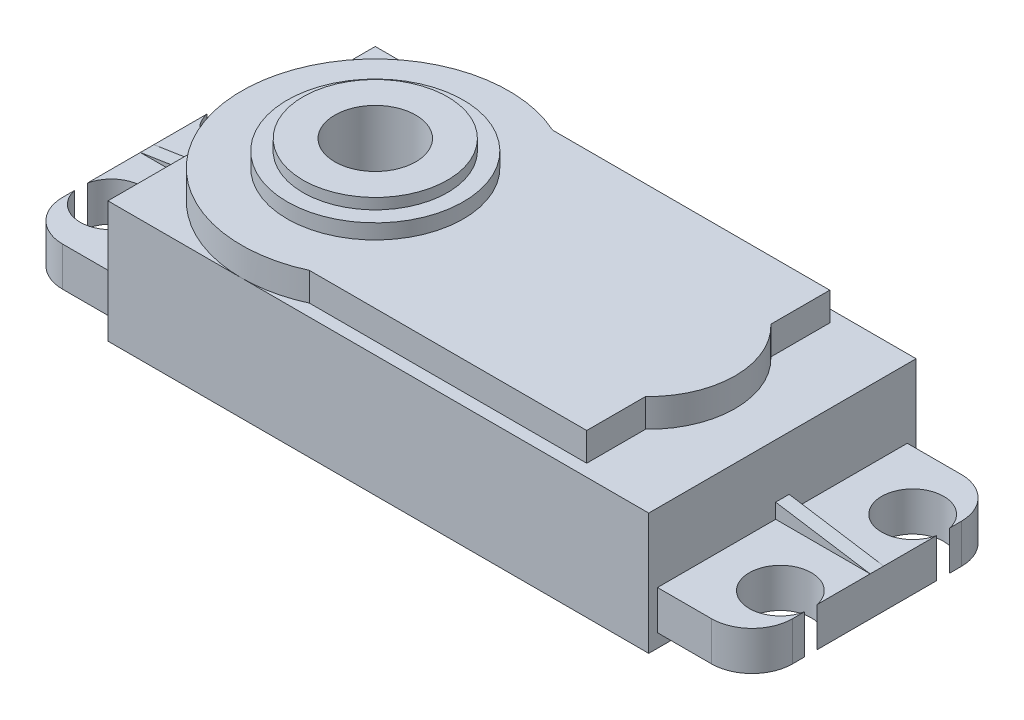
SolidWorks part; units mm, degrees
material "Калифорния"
ref_plane "Спереди" through (0, 0, 0) normal (0, 0, 1) x (1, 0, 0)
ref_plane "Сверху" through (0, 0, 0) normal (0, 1, 0) x (1, 0, 0)
ref_plane "Справа" through (0, 0, 0) normal (1, 0, 0) x (0, 0, -1)
sketch "Эскиз1" plane through (0, 0, 0) normal (0, 1, 0) x (1, 0, 0)
  line L1 (-20.025, -9.9) -> (20.025, -9.9)
  line L2 (-20.025, -9.9) -> (-20.025, 9.9)
  line L3 (-20.025, 9.9) -> (20.025, 9.9)
  line L4 (20.025, -9.9) -> (20.025, 9.9)
  line L5 (-20.025, -9.9) -> (20.025, 9.9) construction
  line L6 (-20.025, 9.9) -> (20.025, -9.9) construction
  point P0 (0, 0)
extrude "Бобышка-Вытянуть1" add sketch "Эскиз1" along normal blind 9
shell "Оболочка1" thickness 1.6
sketch "Эскиз2" plane through (0, 0, 0) normal (0, -1, 0) x (1, 0, 0)
  line L0 (20.025, 9.9) -> (20.025, -9.9) construction
  line L1 (-19.125, -9) -> (19.125, -9)
  line L2 (-19.125, -9) -> (-19.125, 9)
  line L3 (-19.125, 9) -> (19.125, 9)
  line L4 (19.125, -9) -> (19.125, 9)
  line L5 (-19.125, -9) -> (19.125, 9) construction
  line L6 (-19.125, 9) -> (19.125, -9) construction
  line L7 (-20.025, 9.9) -> (20.025, 9.9) construction
  point P0 (0, 0)
  dimension "D1" = 0.9
  dimension "D2" = 0.9
extrude "Вырез-Вытянуть1" cut sketch "Эскиз2" against normal blind 1
sketch "Эскиз3" plane through (0, 9, 0) normal (0, 1, 0) x (1, 0, 0)
  line L0 (-20.025, 9.9) -> (-20.025, -9.9) construction
  line L1 (20.025, 0) -> (16.525, 0) construction
  line L2 (14.5329, 4.6401) -> (14.5329, 9)
  line L3 (20.025, -9.9) -> (20.025, 9.9) construction
  line L4 (14.5329, -9) -> (-6.0007, -9)
  line L5 (14.5329, -9) -> (14.5329, -4.6401)
  line L6 (14.5329, 9) -> (-6.0007, 9)
  arc A0 (-6.0007, 9) -> (-6.0007, -9) centre (-10.125, 0) ccw
  arc A1 (14.5329, -4.6401) -> (14.5329, 4.6401) centre (10.125, 0) ccw
  point P0 (-20.025, 0)
  point P15 (14.5329, 0)
  dimension "D1" = 9.9
extrude "Бобышка-Вытянуть2" add sketch "Эскиз3" along normal blind 2.1
sketch "Эскиз4" plane through (0, 11.1, 0) normal (0, 1, 0) x (1, 0, 0)
  circle A0 centre (-10.125, 0) radius 6.525
extrude "Бобышка-Вытянуть3" add sketch "Эскиз4" along normal blind 1.1
sketch "Эскиз5" plane through (0, 12.2, 0) normal (0, 1, 0) x (1, 0, 0)
  circle A0 centre (-10.125, 0) radius 5.35
extrude "Бобышка-Вытянуть4" add sketch "Эскиз5" along normal blind 0.8
sketch "Эскиз6" plane through (0, 13, 0) normal (0, 1, 0) x (1, 0, 0)
  circle A0 centre (-10.125, 0) radius 3
extrude "Вырез-Вытянуть2" cut sketch "Эскиз6" against normal up to vertex
sketch "Эскиз7" plane through (0, 11.1, 0) normal (0, 1, 0) x (1, 0, 0)
  line L1 (-19, -8.2) -> (19, -8.2) construction
  line L2 (-19, -8.2) -> (-19, 8.2) construction
  line L3 (-19, 8.2) -> (19, 8.2) construction
  line L4 (19, -8.2) -> (19, 8.2) construction
  line L5 (-19, -8.2) -> (19, 8.2) construction
  line L6 (-19, 8.2) -> (19, -8.2) construction
  circle A0 centre (-18.2, 7.4) radius 0.8
  circle A1 centre (18.2, 7.4) radius 0.8
  circle A2 centre (18.2, -7.4) radius 0.8
  circle A3 centre (-18.2, -7.4) radius 0.8
  point P0 (0, 0)
extrude "Вырез-Вытянуть3" cut sketch "Эскиз7" against normal blind 14
sketch "Эскиз8" plane through (0, 7.4, 0) normal (0, -1, 0) x (-1, 0, 0)
  circle A0 centre (18.2, -7.4) radius 1.6
  arc A2 (18.425, -6.6323) -> (18.425, -8.1677) centre (18.2, -7.4) ccw construction
  circle A3 centre (18.2, 7.4) radius 1.6
  circle A4 centre (-18.2, 7.4) radius 1.6
  circle A5 centre (-18.2, -7.4) radius 1.6
  circle A6 centre (-18.2, 7.4) radius 0.8
  circle A7 centre (-18.2, -7.4) radius 0.8
  circle A8 centre (18.2, 7.4) radius 0.8
  circle A9 centre (18.2, -7.4) radius 0.8
  dimension "D1" = 0.8
extrude "Бобышка-Вытянуть5" add sketch "Эскиз8" along normal up to vertex
sketch "Эскиз9" plane through (0, 9, 0) normal (0, 1, 0) x (1, 0, 0)
  circle A0 centre (18.2, 7.4) radius 0.8
  circle A1 centre (18.2, -7.4) radius 0.8
  circle A2 centre (-18.2, -7.4) radius 0.8
  circle A3 centre (-18.2, 7.4) radius 0.8
extrude "Бобышка-Вытянуть6" add sketch "Эскиз9" against normal up to vertex (1.6 mm away)
sketch "Эскиз10" plane through (20.025, 0, 0) normal (1, 0, 0) x (0, 0, -1)
  line L0 (0, 9) -> (0, 1) construction
  line L1 (4.6401, 9) -> (-4.6401, 9) construction
  line L2 (0, 3.9) -> (0, 5) construction
  line L3 (9.25, 1) -> (-9.25, 1)
  line L4 (9.25, 1) -> (9.25, 3.9)
  line L5 (9.25, 3.9) -> (0.5, 3.9)
  line L6 (-9.25, 1) -> (-9.25, 3.9)
  line L7 (-0.5, 3.9) -> (-9.25, 3.9)
  line L9 (-0.5, 3.9) -> (-0.5, 5)
  line L10 (-0.5, 5) -> (0.5, 5)
  line L11 (0.5, 3.9) -> (0.5, 5)
  line L12 (-0.5, 3.9) -> (0.5, 5) construction
  line L13 (-0.5, 5) -> (0.5, 3.9) construction
  point P5 (9.25, 1)
  point P12 (0, 4.45)
  dimension "D1" = 9.25
extrude "Бобышка-Вытянуть7" add sketch "Эскиз10" along normal blind 7
sketch "Эскиз11" plane through (0, 0, 0.5) normal (0, 0, 1) x (1, 0, 0)
  line L0 (20.025, 5) -> (27.025, 3.9)
  line L1 (27.025, 3.9) -> (27.025, 5)
  line L2 (27.025, 5) -> (20.025, 5)
extrude "Вырез-Вытянуть4" cut sketch "Эскиз11" against normal blind 7
sketch "Эскиз12" plane through (0, 3.9, 0) normal (0, 1, 0) x (1, 0, 0)
  line L1 (24.775, -7.2) -> (24.775, -0.5) construction
  line L2 (20.025, -0.5) -> (27.025, -0.5) construction
  line L3 (24.775, 7.2) -> (24.775, 0.5) construction
  line L4 (27.025, 0.5) -> (20.025, 0.5) construction
  circle A0 centre (24.775, -4.9) radius 2.3
  circle A1 centre (24.775, 4.9) radius 2.3
  dimension "D1" = 9.8
  dimension "D2" = 4.6
extrude "Вырез-Вытянуть5" cut sketch "Эскиз12" against normal blind 7
sketch "Эскиз15" plane through (-20.025, 0, 0) normal (-1, 0, 0) x (0, 0, 1)
  line L0 (-0.5, 3.9) -> (-9.25, 3.9)
  line L1 (9.25, 3.9) -> (0.5, 3.9)
  line L2 (9.25, 3.9) -> (9.25, 1)
  line L3 (9.25, 1) -> (-9.25, 1)
  line L4 (-9.25, 3.9) -> (-9.25, 1)
  line L6 (0.5, 3.9) -> (0.5, 5)
  line L7 (0.5, 5) -> (-0.5, 5)
  line L8 (-0.5, 3.9) -> (-0.5, 5)
extrude "Бобышка-Вытянуть8" add sketch "Эскиз15" along normal blind 7
sketch "Эскиз16" plane through (0, 3.9, 0) normal (0, 1, 0) x (1, 0, 0)
  line L0 (24.775, -4.9) -> (24.775, 4.9) construction
  line L4 (-20.025, -4.9) -> (-24.775, -4.9) construction
  line L7 (-20.025, 0) -> (-20.025, -9.9) construction
  line L8 (-20.025, 0.5) -> (-20.025, 9.25) construction
  line L9 (-20.025, 4.9) -> (-24.775, 4.9) construction
  circle A0 centre (-24.775, 4.9) radius 2.3
  circle A1 centre (-24.775, -4.9) radius 2.3
extrude "Вырез-Вытянуть6" cut sketch "Эскиз16" against normal blind 7
fillet "Скругление1" radius 3 4 edges at (-27.025, 2.45, -9.25) (27.025, 2.45, -9.25) (27.025, 2.45, 9.25) (-27.025, 2.45, 9.25)
sketch "Эскиз17" plane through (0, 0, 0.5) normal (0, 0, 1) x (1, 0, 0)
  line L0 (-27.025, 3.9) -> (-20.025, 5)
  line L1 (-20.025, 5) -> (-27.025, 5)
  line L2 (-27.025, 5) -> (-27.025, 3.9)
extrude "Вырез-Вытянуть7" cut sketch "Эскиз17" against normal blind 7
